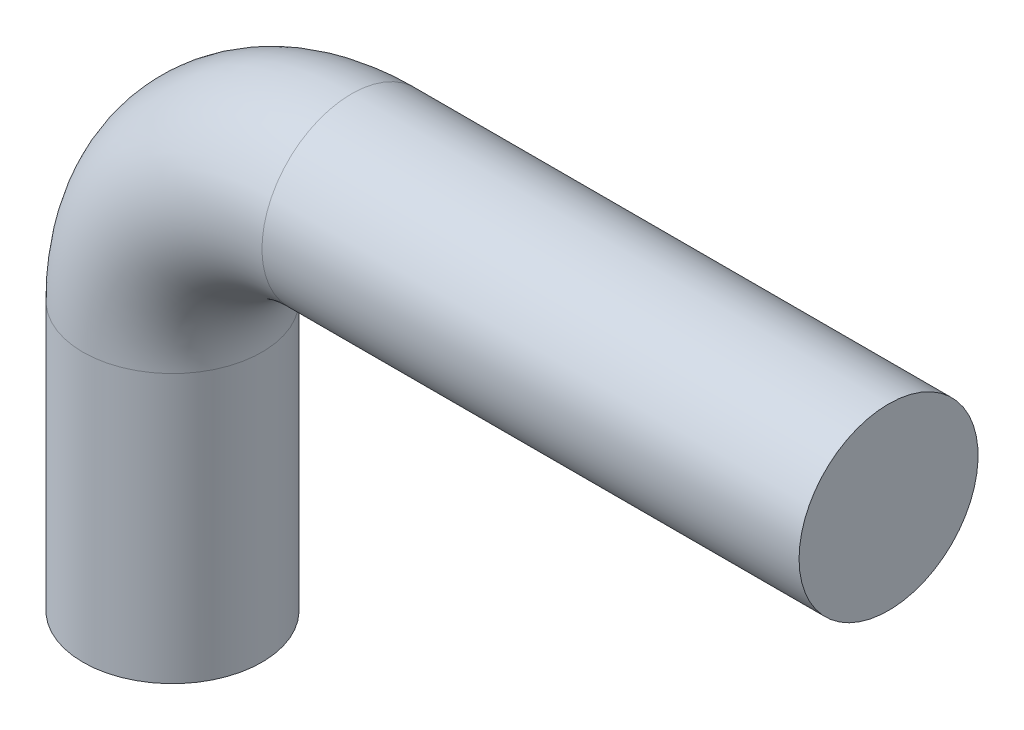
SolidWorks part; units mm, degrees
ref_plane "Front Plane" through (0, 0, 0) normal (0, 0, 1) x (1, 0, 0)
ref_plane "Top Plane" through (0, 0, 0) normal (0, 1, 0) x (1, 0, 0)
ref_plane "Right Plane" through (0, 0, 0) normal (1, 0, 0) x (0, 0, -1)
sketch "Sketch1" plane through (0, 0, 0) normal (0, 0, 1) x (1, 0, 0)
  line L0 (0, 0) -> (0, 15)
  line L1 (10, 25) -> (40, 25)
  arc A0 (0, 15) -> (10, 25) centre (10, 15) cw
  dimension "D1" = 10
  dimension "D2" = 15
  dimension "D3" = 30
sweep "Sweep1" add path "Sketch1" circular profile diameter 10 parameters "D3"=10
